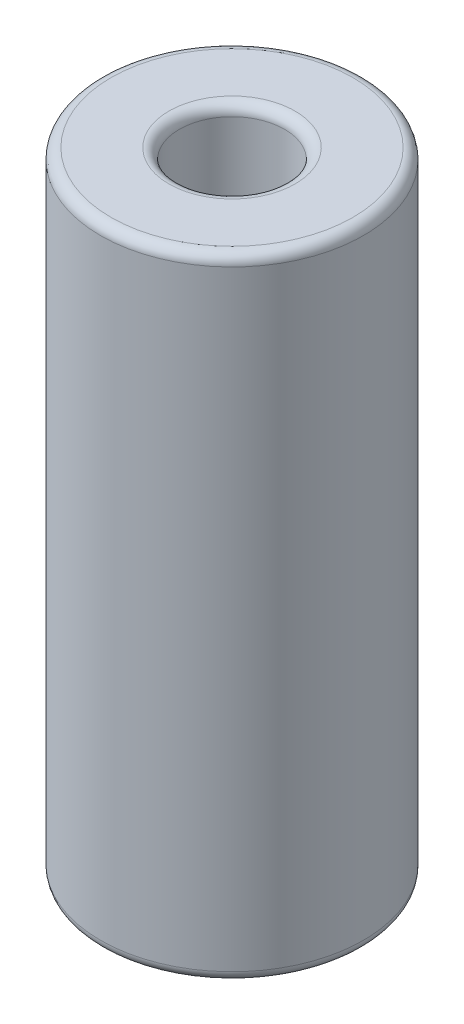
SolidWorks part; units mm, degrees
material "Delrin 2700 NC010, Low Viscosity Acetal Copolymer (SS)"
ref_plane "Front Plane" through (0, 0, 0) normal (0, 0, 1) x (1, 0, 0)
ref_plane "Top Plane" through (0, 0, 0) normal (0, 1, 0) x (1, 0, 0)
ref_plane "Right Plane" through (0, 0, 0) normal (1, 0, 0) x (0, 0, -1)
sketch "Sketch1" plane through (0, 0, 0) normal (0, 1, 0) x (1, 0, 0)
  circle A0 centre (0, 0) radius 12.7
  circle A1 centre (0, 0) radius 31.75
  dimension "D1" = 63.5
  dimension "D2" = 25.4
extrude "Boss-Extrude1" add sketch "Sketch1" along normal blind 152.4
fillet "Fillet1" radius 2.54 4 edges at (0, 0, 12.7) (0, 0, 31.75) (0, 152.4, 31.75) (0, 152.4, 12.7)
